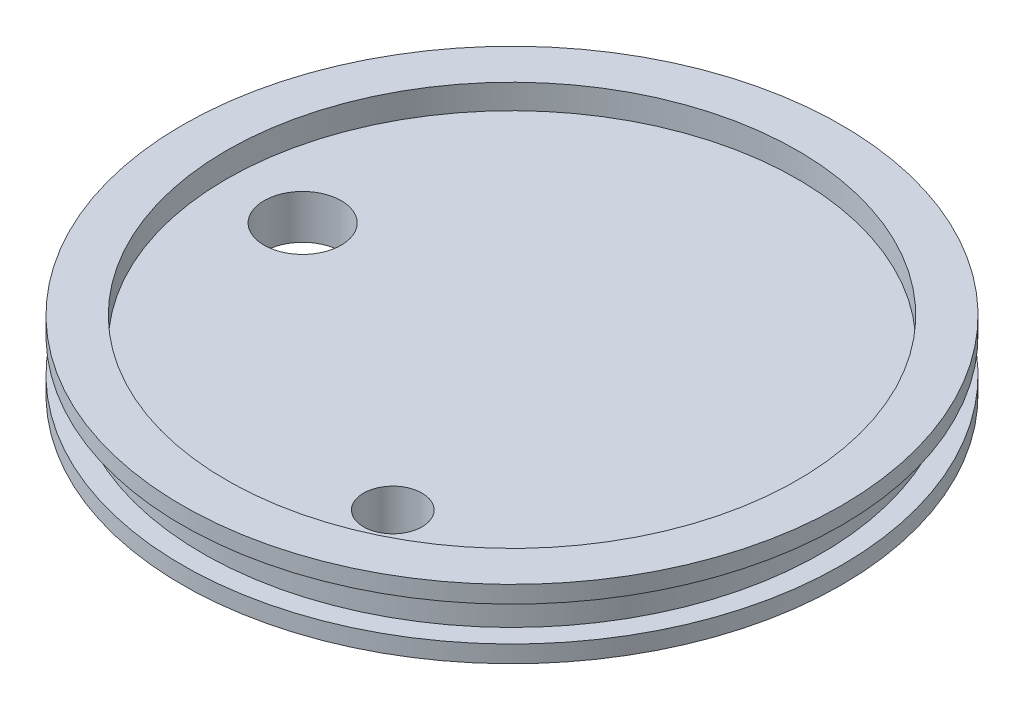
SolidWorks part; units mm, degrees
material "6061-T6 (SS)"
ref_plane "Front Plane" through (0, 0, 0) normal (0, 0, 1) x (1, 0, 0)
ref_plane "Top Plane" through (0, 0, 0) normal (0, 1, 0) x (1, 0, 0)
ref_plane "Right Plane" through (0, 0, 0) normal (1, 0, 0) x (0, 0, -1)
sketch "Sketch1" plane through (0, 0, 0) normal (0, 0, 1) x (1, 0, 0)
  line L0 (0, 48.1922) -> (0, -25.6743) construction
  line L1 (0, 0) -> (47.498, 0)
  line L2 (47.498, 0) -> (47.498, 2.4638)
  line L3 (47.498, 2.4638) -> (44.577, 2.4638)
  line L4 (44.577, 2.4638) -> (44.577, 7.4422)
  line L5 (44.577, 7.4422) -> (47.498, 7.4422)
  line L6 (47.498, 7.4422) -> (47.498, 9.906)
  line L7 (47.498, 9.906) -> (41.148, 9.906)
  line L8 (41.148, 9.906) -> (41.148, 6.35)
  line L9 (41.148, 6.35) -> (0, 6.35)
  line L10 (0, 6.35) -> (0, 0)
  dimension "D1" = 94.996
  dimension "D2" = 4.9784
  dimension "D3" = 2.921
  dimension "D4" = 9.906
  dimension "D5" = 6.35
  dimension "D6" = 6.35
revolve "Revolve1" add sketch "Sketch1" angle 360 about L0
hole_wizard "Pipe Tap Drill for 1/4 Tap1" positions "Sketch2" profile "Sketch3" hole size "1/4" standard "ANSI Inch" end condition through all
sketch "Sketch2" plane through (0, 6.35, 0) normal (0, 1, 0) x (1, 0, 0)
  point P4 (-30.1752, 0)
  point P13 (0, 0)
  dimension "D1" = 30.1752
sketch "Sketch3" plane through (-30.1752, 6.35, 0) normal (1, 0, 0) x (0, 0, 1)
  line L0 (0, 0) -> (0, 6.35)
  line L1 (0, 6.35) -> (5.5626, 6.35)
  line L2 (5.5626, 6.35) -> (5.5626, 0)
  line L5 (5.5626, 0) -> (0, 0)
  line L11 (0, -6.35) -> (0, 107.95) construction
  dimension "Thru Hole Dia." = 11.1252
  dimension "Thru Hole Depth" = 6.35
hole_wizard "Pipe Tap Drill for 1/8 Tap1" positions "Sketch4" profile "Sketch5" hole size "1/8" standard "ANSI Inch" end condition through all
sketch "Sketch4" plane through (0, 6.35, 0) normal (0, 1, 0) x (1, 0, 0)
  line L0 (0, 0) -> (12.1502, -29.3332)
  line L1 (0, 0) -> (0, -37.3592)
  point P16 (12.1502, -29.3332)
  dimension "D1" = 31.75
  dimension "D2" = 22.5
sketch "Sketch5" plane through (12.1502, 6.35, 29.3332) normal (1, 0, 0) x (0, 0, 1)
  line L0 (0, 0) -> (0, 6.35)
  line L1 (0, 6.35) -> (4.2164, 6.35)
  line L2 (4.2164, 6.35) -> (4.2164, 0)
  line L5 (4.2164, 0) -> (0, 0)
  line L11 (0, -6.35) -> (0, 107.95) construction
  dimension "Thru Hole Dia." = 8.4328
  dimension "Thru Hole Depth" = 6.35
fillet "CNC ID Fillet" [suppressed] radius 0.1778
fillet "CNC OD Fillet" [suppressed] radius 0.127
chamfer "CNC Chamfers" [suppressed] distance 0.254 angle 45
fillet "CNC Bore Fillet" [suppressed] radius 0.254
